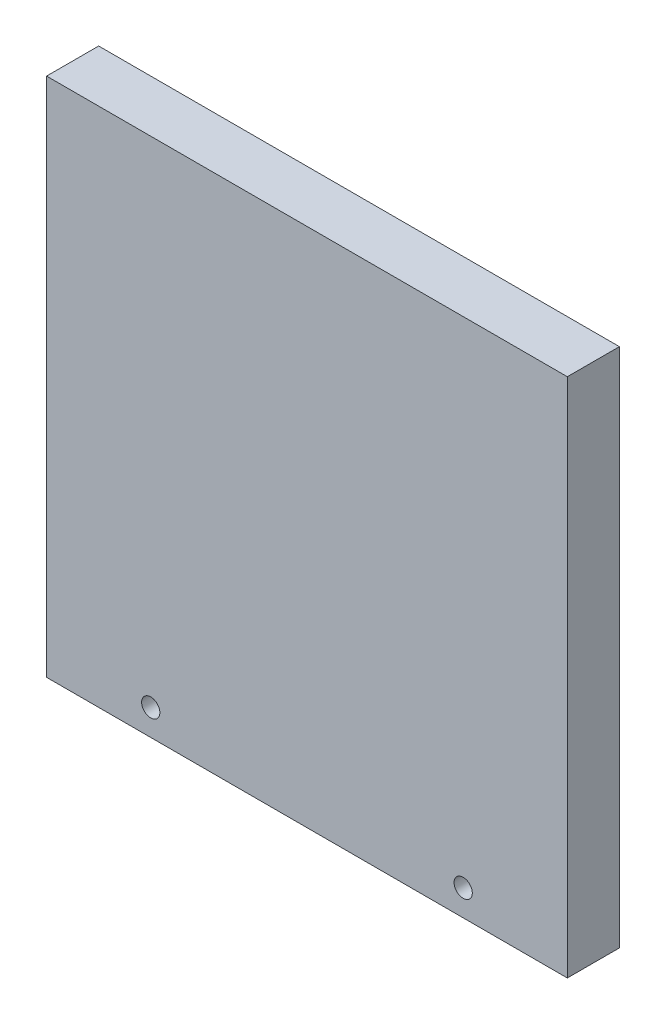
SolidWorks part; units mm, degrees
ref_plane "Front Plane" through (0, 0, 0) normal (0, 0, 1) x (1, 0, 0)
ref_plane "Top Plane" through (0, 0, 0) normal (0, 1, 0) x (1, 0, 0)
ref_plane "Right Plane" through (0, 0, 0) normal (1, 0, 0) x (0, 0, -1)
sketch "Sketch1" plane through (0, 0, 0) normal (0, 0, 1) x (1, 0, 0)
  line L0 (-156.2538, -31.7976) -> (-96.2538, -31.7976)
  line L1 (-176.2538, 63.2024) -> (-76.2538, 63.2024)
  line L2 (-176.2538, 63.2024) -> (-176.2538, -36.7976)
  line L3 (-176.2538, -36.7976) -> (-76.2538, -36.7976)
  line L4 (-76.2538, 63.2024) -> (-76.2538, -36.7976)
  line L5 (-126.2538, 38.9728) -> (-126.2538, 69.7885) construction
  circle A0 centre (-156.2538, -31.7976) radius 1.75
  circle A1 centre (-96.2538, -31.7976) radius 1.75
  point P9 (-126.2538, 63.2024)
  point P11 (-126.2538, -31.7976)
  dimension "D4" = 3.5
  dimension "D1" = 100
  dimension "D2" = 100
  dimension "D3" = 60
  dimension "D5" = 5
extrude "Boss-Extrude1" add sketch "Sketch1" along normal blind 10
ref_plane "Plane1" through (0, 13.2024, 0) normal (0, 1, 0) x (1, 0, 0)
sketch "Sketch2" plane through (0, 13.2024, 0) normal (0, 1, 0) x (1, 0, 0)
  line L0 (-126.2538, 15) -> (-126.2538, 0) construction
  line L1 (-131.7538, 24.5263) -> (-126.2538, 27.7017)
  line L2 (-176.2538, 0) -> (-76.2538, 0) construction
  line L3 (-76.2538, 0) -> (-176.2538, 0)
  line L4 (-126.2538, 27.7017) -> (-120.7538, 24.5263)
  circle A0 centre (-126.2538, 15) radius 4
  circle A1 centre (-126.2538, 15) radius 15
  arc A2 (-176.2538, 0) -> (-139.4891, 22.0588) centre (-176.2538, 41.6667) ccw
  arc A3 (-76.2538, 0) -> (-113.0185, 22.0588) centre (-76.2538, 41.6667) cw
  circle A4 centre (-126.2538, 15) radius 11
  dimension "D1" = 8
  dimension "D2" = 30
  dimension "D3" = 22
  dimension "D4" = 30
extrude "Boss-Extrude2" add sketch "Sketch2" along normal mid plane 8
